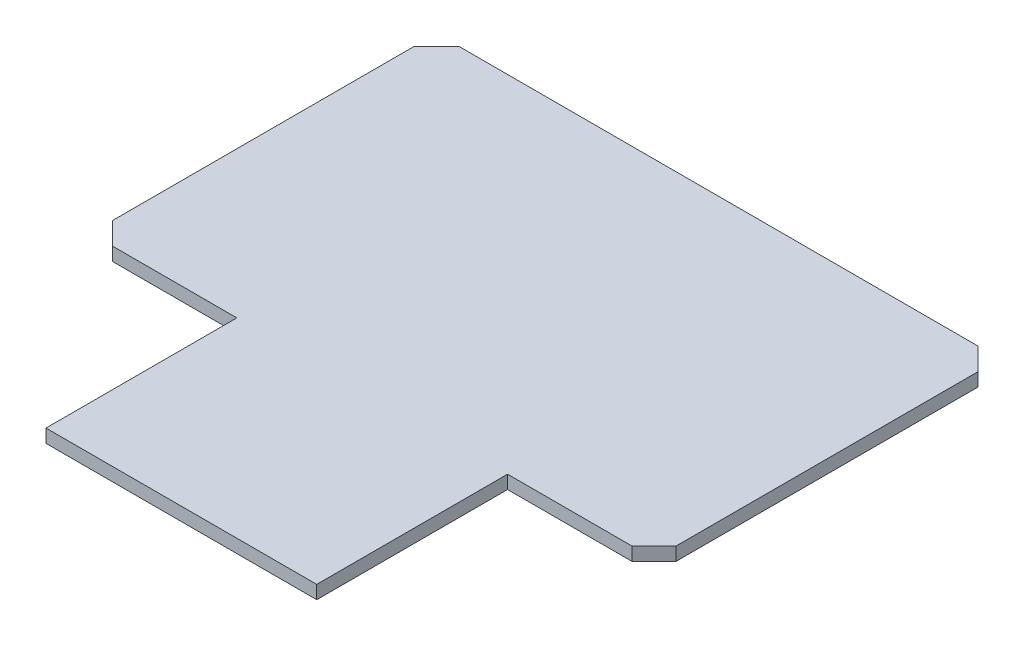
SolidWorks part; units mm, degrees
ref_plane "Plan de face" through (0, 0, 0) normal (0, 0, 1) x (1, 0, 0)
ref_plane "Plan de dessus" through (0, 0, 0) normal (0, 1, 0) x (1, 0, 0)
ref_plane "Plan de droite" through (0, 0, 0) normal (1, 0, 0) x (0, 0, -1)
sketch "Esquisse1" plane through (0, 0, 0) normal (0, 1, 0) x (1, 0, 0)
  line L0 (0, 52.8222) -> (0, -57.5469) construction
  line L1 (-69.3586, 0) -> (112.2589, 0) construction
  line L2 (0, 0) -> (-30.5, 0)
  line L3 (-30.5, 0) -> (-30.5, 43)
  line L4 (-30.5, 43) -> (-63.5, 43)
  line L5 (-63.5, 43) -> (-63.5, 121)
  line L6 (-63.5, 121) -> (63.5, 121)
  line L7 (63.5, 121) -> (63.5, 43)
  line L8 (63.5, 43) -> (30.5, 43)
  line L9 (30.5, 43) -> (30.5, 0)
  line L10 (30.5, 0) -> (0, 0)
  dimension "D1" = 127
  dimension "D2" = 78
  dimension "D3" = 43
  dimension "D4" = 33
extrude "Boss.-Extru.1" add sketch "Esquisse1" along normal blind 3
chamfer "Chanfrein1" distance 5 angle 45 4 edges at (-63.5, 1.5, -43) (63.5, 1.5, -43) (63.5, 1.5, -121) (-63.5, 1.5, -121)
